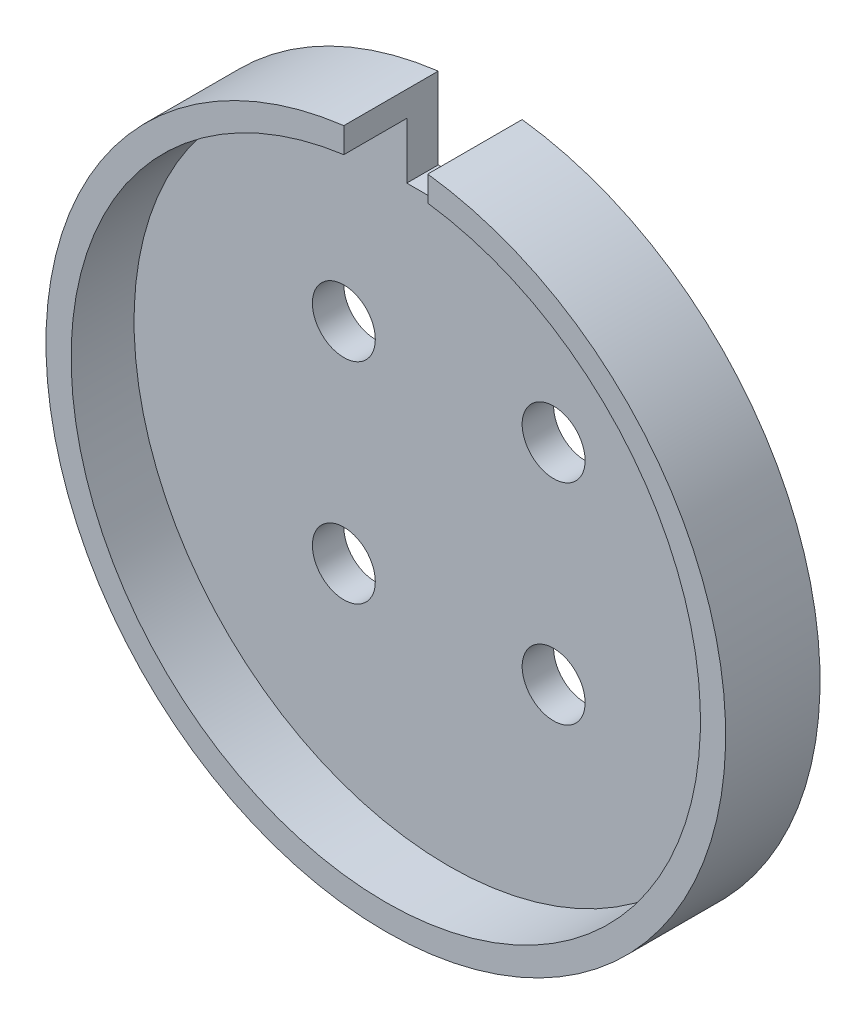
SolidWorks part; units mm, degrees
ref_plane "Alzado" through (0, 0, 0) normal (0, 0, 1) x (1, 0, 0)
ref_plane "Planta" through (0, 0, 0) normal (0, 1, 0) x (1, 0, 0)
ref_plane "Vista lateral" through (0, 0, 0) normal (1, 0, 0) x (0, 0, -1)
sketch "Croquis1" plane through (0, 0, 0) normal (0, 0, 1) x (1, 0, 0)
  line L0 (-46.5215, 2.788) -> (-46.5215, 18.988) construction
  line L1 (-46.5215, 18.988) -> (-48.5215, 18.988) construction
  line L2 (-46.5215, 18.988) -> (-44.5215, 18.988) construction
  line L3 (-46.5215, 2.788) -> (-41.5215, 2.788) construction
  line L8 (-41.5215, 2.788) -> (-41.5215, -2.212) construction
  line L9 (-48.5215, 14.9903) -> (-48.5215, 18.864)
  line L10 (-44.5215, 14.9903) -> (-48.5215, 14.9903)
  line L11 (-44.5215, 14.9903) -> (-44.5215, 18.864)
  circle A2 centre (-41.5215, -2.212) radius 1.5
  circle A3 centre (-51.5215, -2.212) radius 1.5
  circle A4 centre (-51.5215, 7.788) radius 1.5
  circle A5 centre (-41.5215, 7.788) radius 1.5
  arc A8 (-44.5215, 18.864) -> (-48.5215, 18.864) centre (-46.5215, 2.788) cw
  dimension "D1" = 16.2
  dimension "D2" = 2
  dimension "D5" = 16.2
  dimension "D6" = 5
  dimension "D7" = 5
  dimension "D3" = 2
extrude "Saliente-Extruir1" add sketch "Croquis1" along normal blind 1.5
sketch "Croquis2" plane through (0, 0, 1.5) normal (0, 0, 1) x (1, 0, 0)
  line L4 (-48.5215, 18.864) -> (-48.5215, 17.664)
  line L5 (-48.5215, 14.9903) -> (-48.5215, 18.864) construction
  line L6 (-44.5215, 18.864) -> (-44.5215, 17.6638)
  line L7 (-44.5215, 18.864) -> (-44.5215, 14.9903) construction
  line L8 (-46.5215, -13.412) -> (-46.5215, -12.212) construction
  arc A2 (-48.5215, 18.864) -> (-44.5215, 18.864) centre (-46.5215, 2.788) ccw construction
  arc A3 (-48.5215, 17.664) -> (-44.5215, 17.6638) centre (-46.5222, 2.7979) ccw
  arc A4 (-48.5215, 18.864) -> (-44.5215, 18.864) centre (-46.5215, 2.788) ccw
extrude "Saliente-Extruir2" add sketch "Croquis2" along normal blind 3
